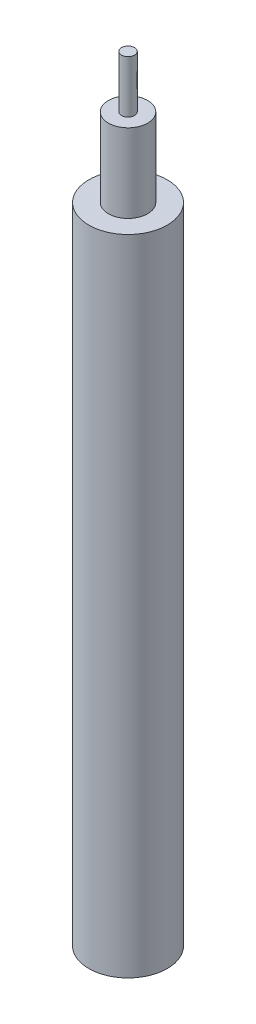
SolidWorks part; units mm, degrees
ref_plane "Front Plane" through (0, 0, 0) normal (0, 0, 1) x (1, 0, 0)
ref_plane "Top Plane" through (0, 0, 0) normal (0, 1, 0) x (1, 0, 0)
ref_plane "Right Plane" through (0, 0, 0) normal (1, 0, 0) x (0, 0, -1)
sketch "Sketch1" plane through (0, 0, 0) normal (0, 1, 0) x (1, 0, 0)
  circle A0 centre (0, 0) radius 2.3813
  dimension "D1" = 4.7625
extrude "Boss-Extrude1" add sketch "Sketch1" against normal blind 9.525
sketch "Sketch2" plane through (0, -9.525, 0) normal (0, -1, 0) x (-1, 0, 0)
  circle A0 centre (0, 0) radius 4.7625
  dimension "D1" = 9.525
extrude "Boss-Extrude2" add sketch "Sketch2" along normal blind 78.105
sketch "Sketch3" plane through (0, 0, 0) normal (0, 1, 0) x (1, 0, 0)
  circle A0 centre (0, 0) radius 0.7937
extrude "Boss-Extrude3" add sketch "Sketch3" along normal blind 6.35
